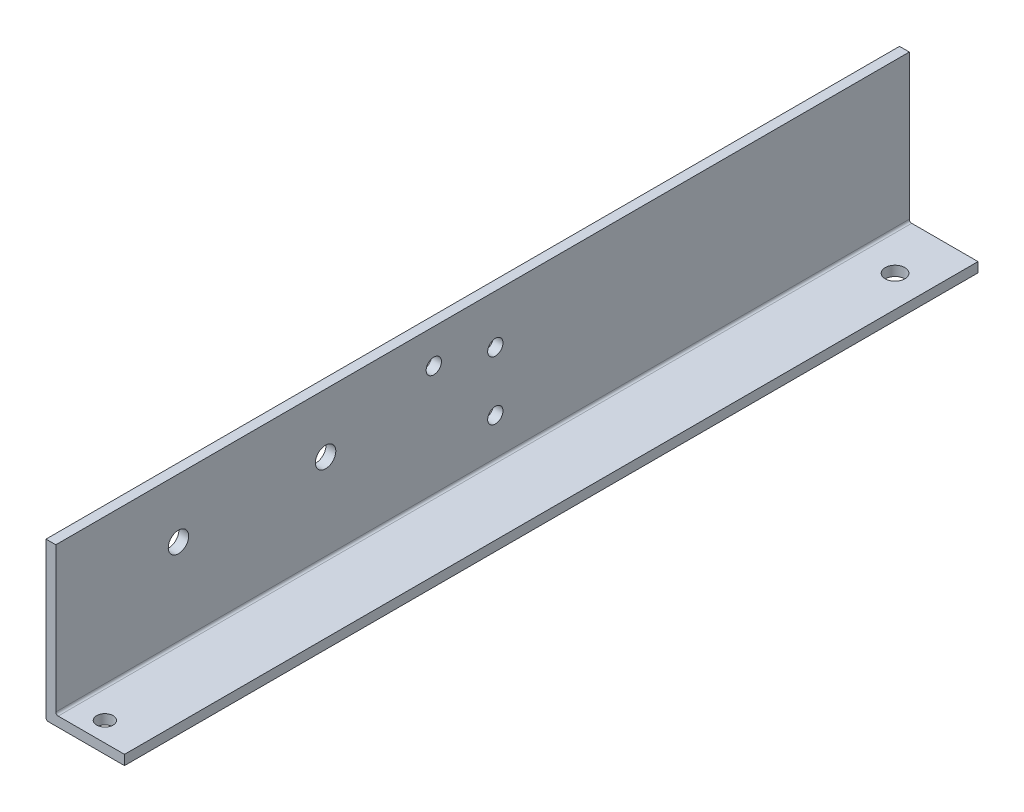
SolidWorks part; units mm, degrees
ref_plane "Front Plane" through (0, 0, 0) normal (0, 0, 1) x (1, 0, 0)
ref_plane "Top Plane" through (0, 0, 0) normal (0, 1, 0) x (1, 0, 0)
ref_plane "Right Plane" through (0, 0, 0) normal (1, 0, 0) x (0, 0, -1)
sketch "Sketch1" plane through (0, 0, 0) normal (0, 0, 1) x (1, 0, 0)
  line L0 (3.175, 50.8) -> (3.175, 3.937)
  line L1 (0.762, 0) -> (25.4, 0)
  line L2 (0, 0.762) -> (0, 50.8)
  line L3 (0, 50.8) -> (3.175, 50.8)
  line L4 (25.4, 0) -> (25.4, 3.175)
  line L5 (3.937, 3.175) -> (25.4, 3.175)
  arc A0 (0, 0.762) -> (0.762, 0) centre (0.762, 0.762) ccw
  arc A1 (3.175, 3.937) -> (3.937, 3.175) centre (3.937, 3.937) ccw
  point P10 (0, 0)
  dimension "D5" = 0.762
  dimension "D6" = 0.762
  dimension "D1" = 25.4
  dimension "D2" = 50.8
  dimension "D3" = 3.175
  dimension "D4" = 3.175
extrude "Boss-Extrude1" add sketch "Sketch1" along normal blind 276.225
sketch "Sketch3" plane through (0, 0, 0) normal (0, -1, 0) x (1, 0, 0)
  line L2 (25.4, 276.225) -> (3.937, 276.225) construction
  line L3 (25.4, 276.225) -> (25.4, 0) construction
  circle A0 centre (12.7, 269.875) radius 2.667
  dimension "D2" = 5.334
  dimension "D1" = 6.35
  dimension "D3" = 12.7
extrude "Cut-Extrude2" cut sketch "Sketch3" against normal up to surface (3.175 mm away) up to face at (14.6685, 3.175, 138.1125)
sketch "Sketch4" plane through (3.175, 0, 0) normal (1, 0, 0) x (0, 0, -1)
  line L1 (-276.225, 50.8) -> (0, 50.8) construction
  line L2 (-276.225, 3.937) -> (-276.225, 50.8) construction
  circle A0 centre (-188.9125, 31.75) radius 3.302 construction
  circle A1 centre (-236.5375, 31.75) radius 3.302 construction
  circle A2 centre (-188.9125, 31.75) radius 3.302
  circle A3 centre (-236.5375, 31.75) radius 3.302
  circle A4 centre (-133.985, 16.002) radius 2.4765
  circle A5 centre (-133.985, 35.052) radius 2.4765
  dimension "D3" = 4.953
  dimension "D4" = 4.953
  dimension "D1" = 142.24
  dimension "D2" = 34.798
  dimension "D6" = 15.748
extrude "Cut-Extrude3" cut sketch "Sketch4" against normal up to surface (3.175 mm away) up to face at (0, 25.781, 138.1125)
sketch "Sketch8" plane through (0, 0, 0) normal (-1, 0, 0) x (0, 0, 1)
  line L0 (276.225, 50.8) -> (0, 50.8) construction
  line L1 (276.225, 3.937) -> (276.225, 50.8) construction
  circle A0 centre (153.8981, 39.7596) radius 2.4765
  dimension "D1" = 4.953
  dimension "D2" = 11.0404
  dimension "D3" = 122.3269
extrude "Cut-Extrude5" cut sketch "Sketch8" against normal up to surface (3.175 mm away) up to face at (3.175, 35.052, 236.5375)
sketch "Sketch9" plane through (0, 3.175, 0) normal (0, 1, 0) x (1, 0, 0)
  line L0 (25.4, 0) -> (3.937, 0) construction
  line L2 (25.4, -276.225) -> (25.4, 0) construction
  circle A0 centre (15.24, -16.6863) radius 3.175
  point P7 (25.4, -18.9936)
  dimension "D1" = 10.16
  dimension "D3" = 6.35
  dimension "D2" = 16.6863
extrude "Cut-Extrude6" cut sketch "Sketch9" against normal up to surface (3.175 mm away) contours A0 up to face at (12.7, 0, 267.208)
